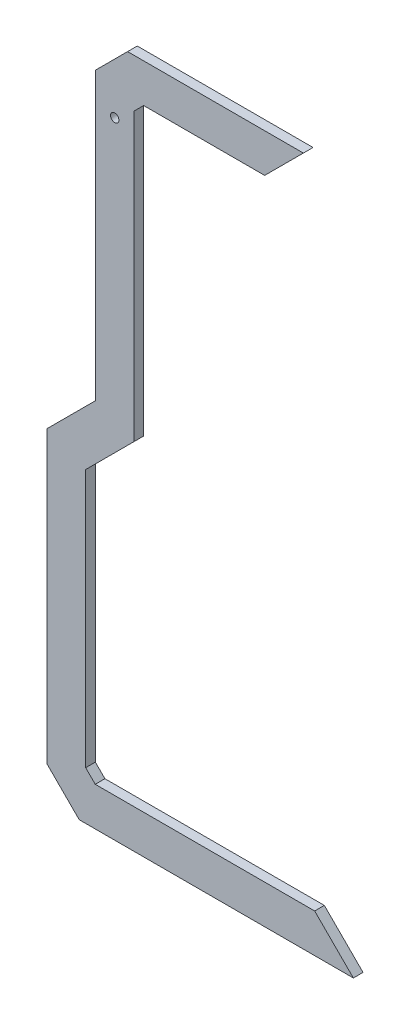
SolidWorks part; units mm, degrees
ref_plane "Front Plane" through (0, 0, 0) normal (0, 0, 1) x (1, 0, 0)
ref_plane "Top Plane" through (0, 0, 0) normal (0, 1, 0) x (1, 0, 0)
ref_plane "Right Plane" through (0, 0, 0) normal (1, 0, 0) x (0, 0, -1)
sketch "Sketch1" plane through (0, 0, 0) normal (0, 0, 1) x (1, 0, 0)
  line L0 (70, -179.754) -> (-15, -179.754) construction
  line L1 (-15, -179.754) -> (-25, -169.754) construction
  line L2 (-25, -169.754) -> (-25, -79.754) construction
  line L3 (-25, -79.754) -> (-10, -64.754) construction
  line L4 (-10, -64.754) -> (-10, 24.0035) construction
  line L5 (-10, 24.0035) -> (0, 34.0035) construction
  line L6 (0, 34.0035) -> (70, 34.0035) construction
  line L7 (70, -179.754) -> (-15, -179.754)
  line L8 (-15, -179.754) -> (-25, -169.754)
  line L9 (-25, -169.754) -> (-25, -79.754)
  line L10 (-25, -79.754) -> (-10, -64.754)
  line L11 (-10, -64.754) -> (-10, 24.0035)
  line L12 (-10, 24.0035) -> (0, 34.0035)
  line L13 (0, 34.0035) -> (54.5, 34.0035)
  line L15 (42.5, 22.0035) -> (4.9706, 22.0035)
  line L16 (4.9706, 22.0035) -> (2, 19.033)
  line L17 (2, 19.033) -> (2, -69.7245)
  line L18 (2, -69.7245) -> (-13, -84.7245)
  line L19 (-13, -84.7245) -> (-13, -164.7834)
  line L20 (-13, -164.7834) -> (-10.0294, -167.754)
  line L21 (-10.0294, -167.754) -> (58, -167.754)
  line L22 (58, -167.754) -> (70, -179.754)
  line L23 (54.5, 34.0035) -> (42.5, 22.0035)
  circle A1 centre (-4, 14.2435) radius 1.3
  dimension "D1" = 12
  dimension "D2" = 12
  dimension "D3" = 12
  dimension "D4" = 12
  dimension "D5" = 12
  dimension "D6" = 12
  dimension "D7" = 12
  dimension "D8" = 45
  dimension "D9" = 54.5
  dimension "D10" = 45
extrude "Extrude1" add sketch "Sketch1" along normal blind 3
